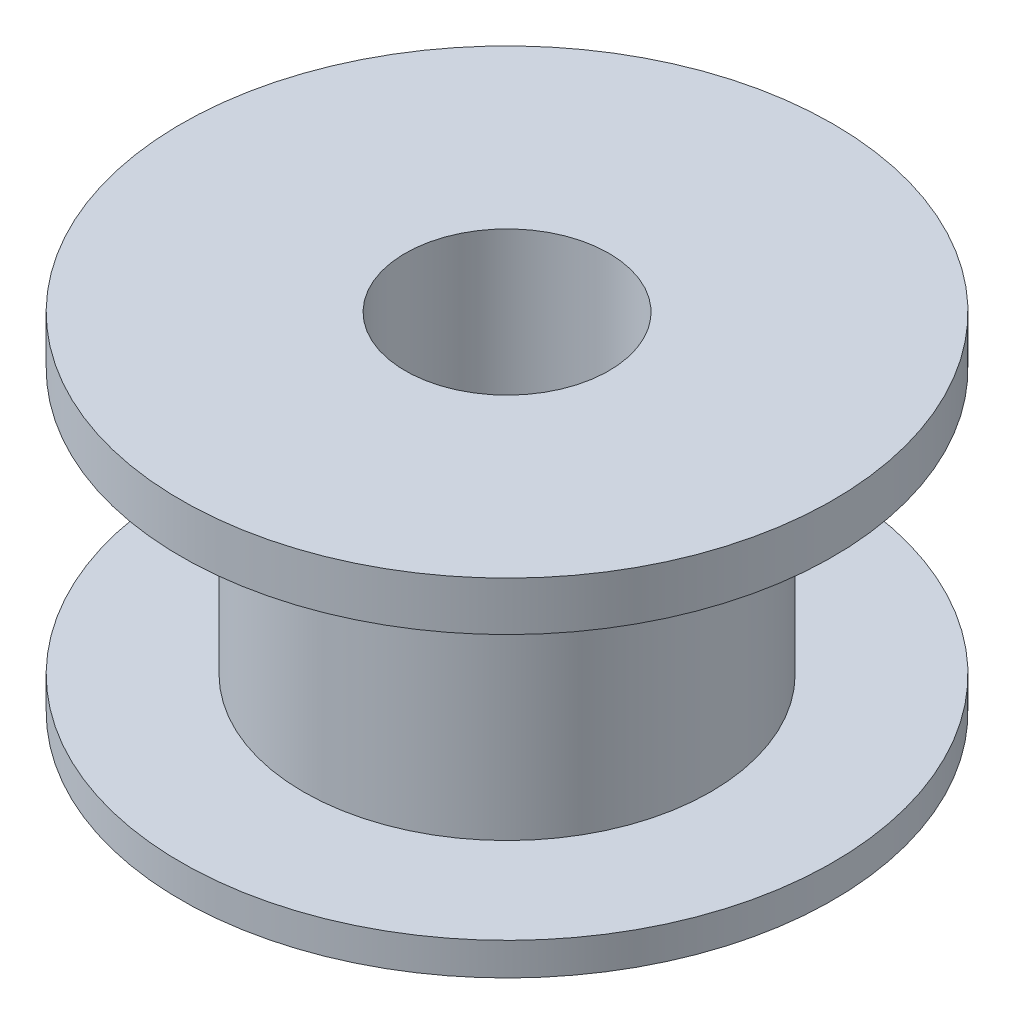
SolidWorks part; units mm, degrees
ref_plane "Front Plane" through (0, 0, 0) normal (0, 0, 1) x (1, 0, 0)
ref_plane "Top Plane" through (0, 0, 0) normal (0, 1, 0) x (1, 0, 0)
ref_plane "Right Plane" through (0, 0, 0) normal (1, 0, 0) x (0, 0, -1)
other "Default"
sketch "Sketch1" plane through (0, 0, 0) normal (0, 0, 1) x (1, 0, 0)
  line L0 (2.5, -4.25) -> (2.5, 4.25)
  line L1 (2.5, 4.25) -> (8, 4.25)
  line L2 (8, 4.25) -> (8, 3.05)
  line L3 (8, 3.05) -> (5, 3.05)
  line L4 (5, 3.05) -> (5, -3.45)
  line L5 (5, -3.45) -> (8, -3.45)
  line L6 (8, -3.45) -> (8, -4.25)
  line L7 (8, -4.25) -> (2.5, -4.25)
  line L8 (0, -4.8815) -> (0, 3.014) construction
  point P3 (2.5, 0)
  dimension "ID" = 5
  dimension "OD" = 16
  dimension "Length" = 8.5
  dimension "SlotSide" = 0.8
  dimension "SlotDiameter" = 10
  dimension "SlotLength" = 6.5
revolve "Revolve1" add sketch "Sketch1" angle 360 about L8
